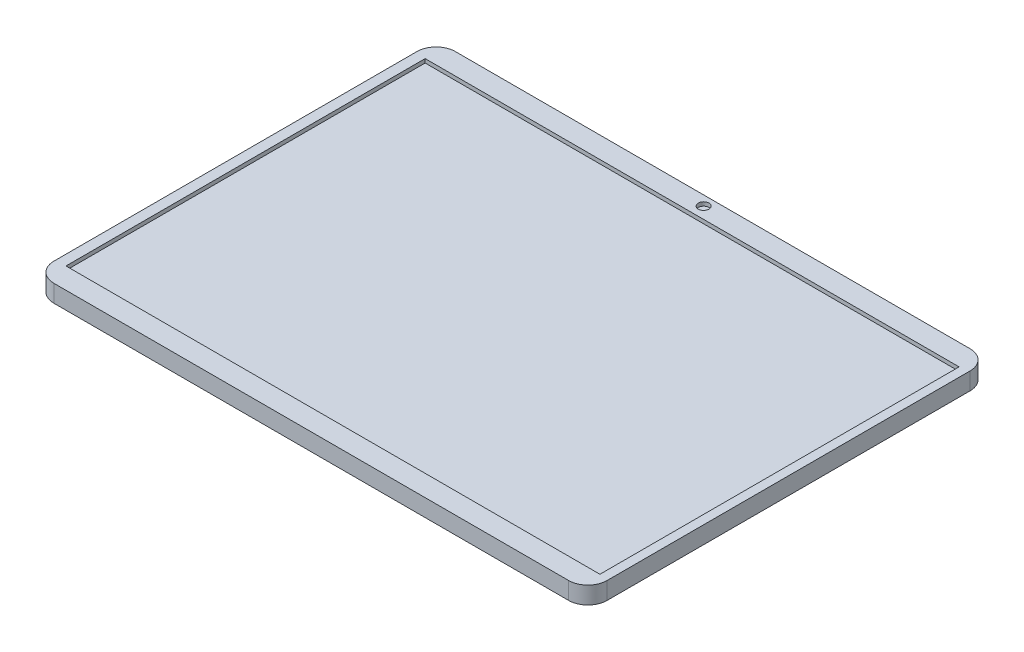
SolidWorks part; units mm, degrees
ref_plane "Front Plane" through (0, 0, 0) normal (0, 0, 1) x (1, 0, 0)
ref_plane "Top Plane" through (0, 0, 0) normal (0, 1, 0) x (1, 0, 0)
ref_plane "Right Plane" through (0, 0, 0) normal (1, 0, 0) x (0, 0, -1)
sketch "Sketch1" plane through (0, 0, 0) normal (0, 1, 0) x (1, 0, 0)
  line L1 (-177.6, 71.8) -> (90.4, 71.8)
  line L2 (-187.6, 61.8) -> (-187.6, -127.2)
  line L3 (-177.6, -137.2) -> (90.4, -137.2)
  line L4 (100.4, 61.8) -> (100.4, -127.2)
  line L5 (-187.6, 71.8) -> (100.4, -137.2) construction
  line L6 (-187.6, -137.2) -> (100.4, 71.8) construction
  arc A0 (-187.6, -127.2) -> (-177.6, -137.2) centre (-177.6, -127.2) ccw
  arc A1 (90.4, -137.2) -> (100.4, -127.2) centre (90.4, -127.2) ccw
  arc A2 (90.4, 71.8) -> (100.4, 61.8) centre (90.4, 61.8) cw
  arc A3 (-177.6, 71.8) -> (-187.6, 61.8) centre (-177.6, 61.8) ccw
  point P4 (-43.6, -32.7)
  dimension "D3" = 10
  dimension "D1" = 288
  dimension "D2" = 209
extrude "Boss-Extrude1" add sketch "Sketch1" along normal blind 9 contours L2 A0 L3 A1 L4 A2 L1 A3
sketch "Sketch2" plane through (0, 9, 0) normal (0, 1, 0) x (1, 0, 0)
  line L0 (-182.2808, 60.7577) -> (-182.2808, -126.2423)
  line L1 (-182.2808, -126.2423) -> (95.7192, -126.2423)
  line L2 (95.7192, -126.2423) -> (95.7192, 60.7577)
  line L3 (95.7192, 60.7577) -> (-182.2808, 60.7577)
  line L4 (-43.2808, 72.7577) -> (-43.2808, 60.7577) construction
  line L8 (-187.2808, 62.7577) -> (-187.2808, -126.2423)
  line L9 (-177.2808, -136.2423) -> (90.7192, -136.2423)
  line L10 (100.7192, -126.2423) -> (100.7192, 62.7577)
  line L11 (90.7192, 72.7577) -> (-177.2808, 72.7577)
  circle A4 centre (-43.2808, 66.7577) radius 2.7668
  arc A8 (-177.2808, 72.7577) -> (-187.2808, 62.7577) centre (-177.2808, 62.7577) ccw
  arc A9 (-187.2808, -126.2423) -> (-177.2808, -136.2423) centre (-177.2808, -126.2423) ccw
  arc A10 (90.7192, -136.2423) -> (100.7192, -126.2423) centre (90.7192, -126.2423) ccw
  arc A11 (100.7192, 62.7577) -> (90.7192, 72.7577) centre (90.7192, 62.7577) ccw
  dimension "D1" = 12
  dimension "D2" = 10
  dimension "D3" = 5
  dimension "D4" = 5
extrude "Cut-Extrude1" cut sketch "Sketch2" against normal blind 2 contours A4 L4 | L4 A4 | L2 L3 L0 L1 | A8 L8 A9 L9 A10 L10 A11 L11
ref_plane "Plane2" through (-187.6, 0, 0) normal (-1, 0, 0) x (0, 0, 1)
sketch "Sketch4" plane through (-187.6, 0, 0) normal (-1, 0, 0) x (0, 0, 1)
  line L0 (-16.8, 9) -> (-16.8, 0) construction
  line L1 (23.2, 9) -> (23.2, 0) construction
  line L2 (-6.8, 4.5) -> (13.2, 4.5) construction
  line L3 (3.2, 9) -> (3.2, 0) construction
  line L4 (-61.8, 0) -> (127.2, 0)
  line L5 (127.2, 0) -> (127.2, 9)
  line L6 (127.2, 9) -> (-61.8, 9)
  line L7 (-61.8, 9) -> (-61.8, 0)
  line L8 (-61.8, 0) -> (127.2, 0)
  line L10 (127.2, 9) -> (-61.8, 9)
  line L12 (-71.8, 0) -> (-61.8, 0)
  line L13 (-61.8, 0) -> (-61.8, 9)
  line L14 (-61.8, 9) -> (-71.8, 9)
  line L15 (-71.8, 9) -> (-71.8, 0)
  line L16 (-71.8, 0) -> (-61.8, 0)
  line L18 (-61.8, 9) -> (-71.8, 9)
  line L19 (-71.8, 9) -> (-71.8, 0)
  line L20 (127.2, 0) -> (137.2, 0)
  line L21 (137.2, 0) -> (137.2, 9)
  line L22 (137.2, 9) -> (127.2, 9)
  line L23 (127.2, 9) -> (127.2, 0)
  line L24 (127.2, 0) -> (137.2, 0)
  line L25 (137.2, 0) -> (137.2, 9)
  line L26 (137.2, 9) -> (127.2, 9)
  line L28 (-6.8, 9) -> (-6.8, 0) construction
  line L29 (13.2, 9) -> (13.2, 0) construction
  line L30 (-16.8, 2.5) -> (23.2, 2.5) construction
  line L31 (-16.8, 6.5) -> (23.2, 6.5) construction
  line L32 (-16.8, 4.5) -> (23.2, 4.5) construction
  line L33 (-16.8, 6.5) -> (-6.8, 6.5)
  line L34 (-16.8, 6.5) -> (-16.8, 2.5)
  line L35 (-16.8, 2.5) -> (-6.8, 2.5)
  line L36 (-6.8, 6.5) -> (-6.8, 2.5)
  line L39 (23.2, 2.5) -> (13.2, 2.5)
  line L40 (23.2, 2.5) -> (23.2, 6.5)
  line L41 (23.2, 6.5) -> (13.2, 6.5)
  line L42 (13.2, 2.5) -> (13.2, 6.5)
  point P12 (23.2, 4.5)
  point P27 (-11.8, 4.5)
  point P30 (18.2, 4.5)
  dimension "D4" = 55
  dimension "D5" = 40
  dimension "D6" = 20
  dimension "D7" = 10
  dimension "D8" = 10
  dimension "D1" = 0
  dimension "D2" = 0
  dimension "D3" = 0
  dimension "D9" = 2
  dimension "D10" = 2
extrude "Cut-Extrude2" cut sketch "Sketch4" against normal blind 2 draft 19 contours L36 L33 L34 L35 | L42 L39 L40 L41
ref_plane "Plane3" through (100.4, 0, 0) normal (1, 0, 0) x (0, 0, -1)
sketch "Sketch5" plane through (100.4, 0, 0) normal (1, 0, 0) x (0, 0, -1)
  line L0 (16.8, 9) -> (16.8, 0) construction
  line L1 (-23.2, 9) -> (-23.2, 0) construction
  line L2 (-23.2, 4.5) -> (16.8, 4.5) construction
  line L4 (-127.2, 0) -> (61.8, 0)
  line L5 (61.8, 0) -> (61.8, 9)
  line L6 (61.8, 9) -> (-127.2, 9)
  line L7 (-127.2, 9) -> (-127.2, 0)
  line L8 (-127.2, 0) -> (61.8, 0)
  line L10 (61.8, 9) -> (-127.2, 9)
  line L12 (-137.2, 0) -> (-127.2, 0)
  line L13 (-127.2, 0) -> (-127.2, 9)
  line L14 (-127.2, 9) -> (-137.2, 9)
  line L15 (-137.2, 9) -> (-137.2, 0)
  line L16 (-137.2, 0) -> (-127.2, 0)
  line L18 (-127.2, 9) -> (-137.2, 9)
  line L19 (-137.2, 9) -> (-137.2, 0)
  line L20 (61.8, 0) -> (71.8, 0)
  line L21 (71.8, 0) -> (71.8, 9)
  line L22 (71.8, 9) -> (61.8, 9)
  line L23 (61.8, 9) -> (61.8, 0)
  line L24 (61.8, 0) -> (71.8, 0)
  line L25 (71.8, 0) -> (71.8, 9)
  line L26 (71.8, 9) -> (61.8, 9)
  line L28 (-23.2, 4.5) -> (16.8, 4.5)
  line L29 (-23.2, 4.5) -> (-23.2, 6.5)
  line L30 (-23.2, 6.5) -> (16.8, 6.5)
  line L31 (16.8, 4.5) -> (16.8, 6.5)
  line L32 (-23.2, 4.5) -> (16.8, 6.5) construction
  line L33 (-23.2, 6.5) -> (16.8, 4.5) construction
  point P16 (-3.2, 5.5)
  dimension "D4" = 55
  dimension "D5" = 40
  dimension "D6" = 2
  dimension "D1" = 0
  dimension "D2" = 0
  dimension "D3" = 0
